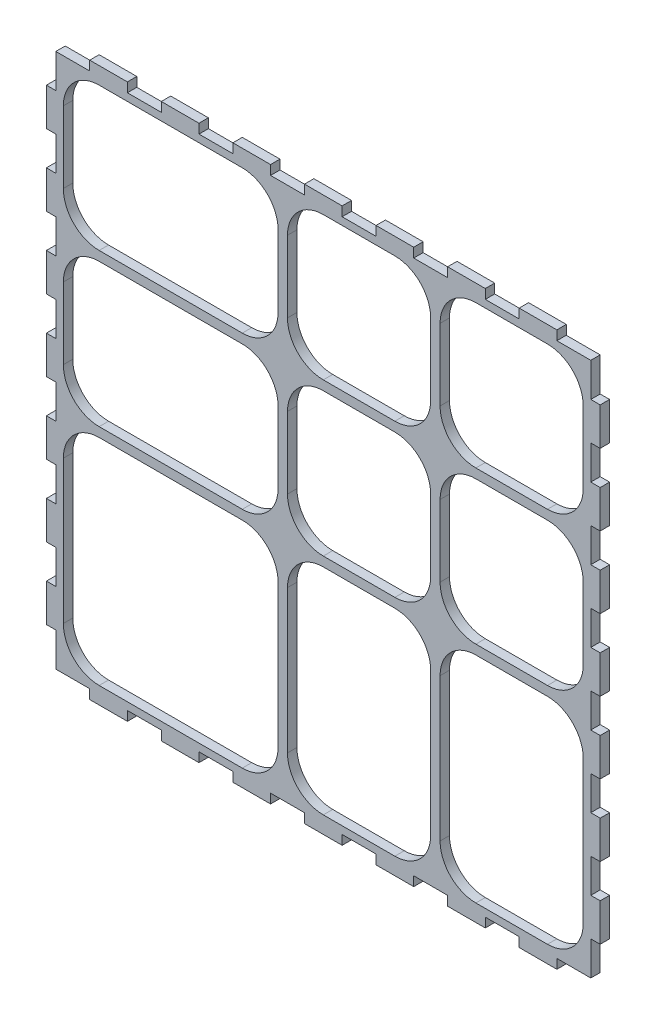
SolidWorks part; units mm, degrees
material "Beech"
ref_plane "Front" through (0, 0, 0) normal (0, 0, 1) x (1, 0, 0)
ref_plane "Top" through (0, 0, 0) normal (0, 1, 0) x (1, 0, 0)
ref_plane "Right" through (0, 0, 0) normal (1, 0, 0) x (0, 0, -1)
sketch "Sketch1" plane through (0, 0, 0) normal (0, 0, 1) x (1, 0, 0)
  line L0 (-71, 71) -> (71, 71) construction
  line L1 (-73.5, -73.5) -> (73.5, -73.5) construction
  line L2 (-73.5, -73.5) -> (-73.5, 73.5) construction
  line L3 (-73.5, 73.5) -> (73.5, 73.5) construction
  line L4 (73.5, -73.5) -> (73.5, 73.5) construction
  line L5 (-73.5, -73.5) -> (73.5, 73.5) construction
  line L6 (-73.5, 73.5) -> (73.5, -73.5) construction
  line L7 (71, -71) -> (71, 71) construction
  line L8 (-71, -71) -> (71, -71) construction
  line L9 (-71, -71) -> (-71, 71) construction
  line L10 (-73.5, 0) -> (-73.5, 5)
  line L11 (-73.5, 5) -> (-71, 5)
  line L12 (-71, 5) -> (-71, 14)
  line L13 (-71, 14) -> (-73.5, 14)
  line L14 (-73.5, 14) -> (-73.5, 24)
  line L15 (-73.5, 24) -> (-71, 24)
  line L16 (-71, 24) -> (-71, 33)
  line L17 (-71, 33) -> (-73.5, 33)
  line L18 (-73.5, 33) -> (-73.5, 43)
  line L19 (-73.5, 43) -> (-71, 43)
  line L20 (-71, 43) -> (-71, 52)
  line L21 (-71, 52) -> (-73.5, 52)
  line L22 (-73.5, 52) -> (-73.5, 62)
  line L23 (-73.5, 62) -> (-71, 62)
  line L24 (-71, 62) -> (-71, 71)
  line L25 (5, 73.5) -> (5, 71)
  line L26 (5, 71) -> (14, 71)
  line L27 (62, 71) -> (71, 71)
  line L28 (24, 71) -> (33, 71)
  line L29 (14, 73.5) -> (24, 73.5)
  line L30 (33, 73.5) -> (43, 73.5)
  line L31 (33, 71) -> (33, 73.5)
  line L32 (52, 71) -> (52, 73.5)
  line L33 (62, 73.5) -> (62, 71)
  line L34 (43, 73.5) -> (43, 71)
  line L35 (-5, 73.5) -> (5, 73.5)
  line L36 (24, 73.5) -> (24, 71)
  line L37 (14, 71) -> (14, 73.5)
  line L38 (43, 71) -> (52, 71)
  line L39 (52, 73.5) -> (62, 73.5)
  line L40 (0, 16.6882) -> (0, -16.401) construction
  line L41 (-21.4019, 0) -> (21.4019, 0) construction
  line L42 (71, 62) -> (71, 71)
  line L43 (73.5, 62) -> (71, 62)
  line L44 (73.5, 52) -> (73.5, 62)
  line L45 (71, 52) -> (73.5, 52)
  line L46 (71, 43) -> (71, 52)
  line L47 (73.5, 43) -> (71, 43)
  line L48 (73.5, 33) -> (73.5, 43)
  line L49 (71, 33) -> (73.5, 33)
  line L50 (71, 24) -> (71, 33)
  line L51 (73.5, 24) -> (71, 24)
  line L52 (73.5, 14) -> (73.5, 24)
  line L53 (71, 14) -> (73.5, 14)
  line L54 (71, 5) -> (71, 14)
  line L55 (73.5, 5) -> (71, 5)
  line L56 (73.5, 0) -> (73.5, 5)
  line L57 (-62, 71) -> (-71, 71)
  line L58 (-62, 73.5) -> (-62, 71)
  line L59 (-52, 73.5) -> (-62, 73.5)
  line L60 (-52, 71) -> (-52, 73.5)
  line L61 (-43, 71) -> (-52, 71)
  line L62 (-43, 73.5) -> (-43, 71)
  line L63 (-33, 73.5) -> (-43, 73.5)
  line L64 (-33, 71) -> (-33, 73.5)
  line L65 (-24, 71) -> (-33, 71)
  line L66 (-24, 73.5) -> (-24, 71)
  line L67 (-14, 73.5) -> (-24, 73.5)
  line L68 (-14, 71) -> (-14, 73.5)
  line L69 (-5, 71) -> (-14, 71)
  line L70 (-5, 73.5) -> (-5, 71)
  line L71 (73.5, 0) -> (73.5, -5)
  line L72 (73.5, -5) -> (71, -5)
  line L73 (71, -5) -> (71, -14)
  line L74 (71, -14) -> (73.5, -14)
  line L75 (73.5, -14) -> (73.5, -24)
  line L76 (73.5, -24) -> (71, -24)
  line L77 (71, -24) -> (71, -33)
  line L78 (71, -33) -> (73.5, -33)
  line L79 (73.5, -33) -> (73.5, -43)
  line L80 (73.5, -43) -> (71, -43)
  line L81 (71, -43) -> (71, -52)
  line L82 (71, -52) -> (73.5, -52)
  line L83 (73.5, -52) -> (73.5, -62)
  line L84 (73.5, -62) -> (71, -62)
  line L85 (71, -62) -> (71, -71)
  line L86 (62, -71) -> (71, -71)
  line L87 (62, -73.5) -> (62, -71)
  line L88 (52, -73.5) -> (62, -73.5)
  line L89 (52, -71) -> (52, -73.5)
  line L90 (43, -71) -> (52, -71)
  line L91 (43, -73.5) -> (43, -71)
  line L92 (33, -73.5) -> (43, -73.5)
  line L93 (33, -71) -> (33, -73.5)
  line L94 (24, -71) -> (33, -71)
  line L95 (24, -73.5) -> (24, -71)
  line L96 (14, -73.5) -> (24, -73.5)
  line L97 (14, -71) -> (14, -73.5)
  line L98 (5, -71) -> (14, -71)
  line L99 (5, -73.5) -> (5, -71)
  line L100 (-5, -73.5) -> (5, -73.5)
  line L101 (-5, -73.5) -> (-5, -71)
  line L102 (-5, -71) -> (-14, -71)
  line L103 (-14, -71) -> (-14, -73.5)
  line L104 (-14, -73.5) -> (-24, -73.5)
  line L105 (-24, -73.5) -> (-24, -71)
  line L106 (-24, -71) -> (-33, -71)
  line L107 (-33, -71) -> (-33, -73.5)
  line L108 (-33, -73.5) -> (-43, -73.5)
  line L109 (-43, -73.5) -> (-43, -71)
  line L110 (-43, -71) -> (-52, -71)
  line L111 (-52, -71) -> (-52, -73.5)
  line L112 (-52, -73.5) -> (-62, -73.5)
  line L113 (-62, -73.5) -> (-62, -71)
  line L114 (-62, -71) -> (-71, -71)
  line L115 (-71, -62) -> (-71, -71)
  line L116 (-73.5, -62) -> (-71, -62)
  line L117 (-73.5, -52) -> (-73.5, -62)
  line L118 (-71, -52) -> (-73.5, -52)
  line L119 (-71, -43) -> (-71, -52)
  line L120 (-73.5, -43) -> (-71, -43)
  line L121 (-73.5, -33) -> (-73.5, -43)
  line L122 (-71, -33) -> (-73.5, -33)
  line L123 (-71, -24) -> (-71, -33)
  line L124 (-73.5, -24) -> (-71, -24)
  line L125 (-73.5, -14) -> (-73.5, -24)
  line L126 (-71, -14) -> (-73.5, -14)
  line L127 (-71, -5) -> (-71, -14)
  line L128 (-73.5, -5) -> (-71, -5)
  line L129 (-73.5, 0) -> (-73.5, -5)
  line L130 (-9.5, 59.5) -> (-9.5, 40.5)
  line L131 (69, 69) -> (31, 69) construction
  line L132 (69, 69) -> (69, 31) construction
  line L133 (69, 31) -> (31, 31) construction
  line L134 (31, 69) -> (31, 31) construction
  line L135 (69, 69) -> (31, 31) construction
  line L136 (69, 31) -> (31, 69) construction
  line L137 (40.5, 69) -> (59.5, 69)
  line L138 (31, 59.5) -> (31, 40.5)
  line L139 (40.5, 31) -> (59.5, 31)
  line L140 (69, 59.5) -> (69, 40.5)
  line L141 (31, 69) -> (69, 31) construction
  line L142 (31, 31) -> (69, 69) construction
  line L143 (0, 69) -> (19, 69)
  line L144 (28.5, 59.5) -> (28.5, 40.5)
  line L145 (0, 31) -> (19, 31)
  line L146 (-9.5, 19) -> (-9.5, 0)
  line L147 (0, 28.5) -> (19, 28.5)
  line L148 (28.5, 19) -> (28.5, 0)
  line L149 (0, -9.5) -> (19, -9.5)
  line L150 (31, 19) -> (31, 0)
  line L151 (40.5, 28.5) -> (59.5, 28.5)
  line L152 (69, 19) -> (69, 0)
  line L153 (40.5, -9.5) -> (59.5, -9.5)
  line L154 (-69, 19) -> (-69, 0)
  line L155 (-69, 69) -> (-12, 69) construction
  line L156 (-69, 69) -> (-69, 31) construction
  line L157 (-69, 31) -> (-12, 31) construction
  line L158 (-12, 69) -> (-12, 31) construction
  line L159 (-69, 69) -> (-12, 31) construction
  line L160 (-69, 31) -> (-12, 69) construction
  line L161 (-59.5, 69) -> (-21.5, 69)
  line L162 (-69, 59.5) -> (-69, 40.5)
  line L163 (-59.5, 31) -> (-21.5, 31)
  line L164 (-12, 59.5) -> (-12, 40.5)
  line L165 (-69, 69) -> (-12, 31) construction
  line L166 (-69, 31) -> (-12, 69) construction
  line L167 (-59.5, 28.5) -> (-21.5, 28.5)
  line L168 (-12, 19) -> (-12, 0)
  line L169 (-59.5, -9.5) -> (-21.5, -9.5)
  line L170 (-9.5, -21.5) -> (-9.5, -59.5)
  line L171 (69, -69) -> (31, -69) construction
  line L172 (69, -69) -> (69, -12) construction
  line L173 (69, -12) -> (31, -12) construction
  line L174 (31, -69) -> (31, -12) construction
  line L175 (69, -69) -> (31, -12) construction
  line L176 (69, -12) -> (31, -69) construction
  line L177 (40.5, -12) -> (59.5, -12)
  line L178 (31, -21.5) -> (31, -59.5)
  line L179 (40.5, -69) -> (59.5, -69)
  line L180 (69, -21.5) -> (69, -59.5)
  line L181 (31, -12) -> (69, -69) construction
  line L182 (31, -69) -> (69, -12) construction
  line L183 (0, -12) -> (19, -12)
  line L184 (28.5, -21.5) -> (28.5, -59.5)
  line L185 (0, -69) -> (19, -69)
  line L187 (-69, -12) -> (-12, -12) construction
  line L188 (-69, -12) -> (-69, -69) construction
  line L189 (-69, -69) -> (-12, -69) construction
  line L190 (-12, -12) -> (-12, -69) construction
  line L191 (-69, -12) -> (-12, -69) construction
  line L192 (-69, -69) -> (-12, -12) construction
  line L193 (-59.5, -12) -> (-21.5, -12)
  line L194 (-69, -21.5) -> (-69, -59.5)
  line L195 (-59.5, -69) -> (-21.5, -69)
  line L196 (-12, -21.5) -> (-12, -59.5)
  line L197 (-69, -12) -> (-12, -69) construction
  line L198 (-69, -69) -> (-12, -12) construction
  arc A49 (59.5, 69) -> (69, 59.5) centre (59.5, 59.5) cw
  arc A50 (59.5, 31) -> (69, 40.5) centre (59.5, 40.5) ccw
  arc A51 (31, 40.5) -> (40.5, 31) centre (40.5, 40.5) ccw
  arc A52 (40.5, 69) -> (31, 59.5) centre (40.5, 59.5) ccw
  arc A53 (0, 69) -> (-9.5, 59.5) centre (0, 59.5) ccw
  arc A54 (-9.5, 40.5) -> (0, 31) centre (0, 40.5) ccw
  arc A55 (19, 69) -> (28.5, 59.5) centre (19, 59.5) cw
  arc A56 (19, 31) -> (28.5, 40.5) centre (19, 40.5) ccw
  arc A57 (0, 28.5) -> (-9.5, 19) centre (0, 19) ccw
  arc A58 (-9.5, 0) -> (0, -9.5) centre (0, 0) ccw
  arc A59 (19, 28.5) -> (28.5, 19) centre (19, 19) cw
  arc A60 (19, -9.5) -> (28.5, 0) centre (19, 0) ccw
  arc A61 (40.5, 28.5) -> (31, 19) centre (40.5, 19) ccw
  arc A62 (31, 0) -> (40.5, -9.5) centre (40.5, 0) ccw
  arc A63 (59.5, 28.5) -> (69, 19) centre (59.5, 19) cw
  arc A64 (59.5, -9.5) -> (69, 0) centre (59.5, 0) ccw
  arc A65 (-21.5, 31) -> (-12, 40.5) centre (-21.5, 40.5) ccw
  arc A66 (-21.5, 69) -> (-12, 59.5) centre (-21.5, 59.5) cw
  arc A67 (-59.5, 69) -> (-69, 59.5) centre (-59.5, 59.5) ccw
  arc A68 (-69, 40.5) -> (-59.5, 31) centre (-59.5, 40.5) ccw
  arc A69 (-69, 0) -> (-59.5, -9.5) centre (-59.5, 0) ccw
  arc A70 (-59.5, 28.5) -> (-69, 19) centre (-59.5, 19) ccw
  arc A71 (-21.5, 28.5) -> (-12, 19) centre (-21.5, 19) cw
  arc A72 (-21.5, -9.5) -> (-12, 0) centre (-21.5, 0) ccw
  arc A73 (59.5, -12) -> (69, -21.5) centre (59.5, -21.5) cw
  arc A74 (59.5, -69) -> (69, -59.5) centre (59.5, -59.5) ccw
  arc A75 (31, -59.5) -> (40.5, -69) centre (40.5, -59.5) ccw
  arc A76 (40.5, -12) -> (31, -21.5) centre (40.5, -21.5) ccw
  arc A77 (0, -12) -> (-9.5, -21.5) centre (0, -21.5) ccw
  arc A78 (-9.5, -59.5) -> (0, -69) centre (0, -59.5) ccw
  arc A79 (19, -12) -> (28.5, -21.5) centre (19, -21.5) cw
  arc A80 (19, -69) -> (28.5, -59.5) centre (19, -59.5) ccw
  arc A81 (-21.5, -69) -> (-12, -59.5) centre (-21.5, -59.5) ccw
  arc A82 (-69, -59.5) -> (-59.5, -69) centre (-59.5, -59.5) ccw
  arc A83 (-59.5, -12) -> (-69, -21.5) centre (-59.5, -21.5) ccw
  arc A84 (-21.5, -12) -> (-12, -21.5) centre (-21.5, -21.5) cw
  point P0 (0, 0)
  point P73 (0, 73.5)
  point P135 (50, 50)
  point P137 (50, 50)
  point P189 (-40.5, 50)
  point P191 (-40.5, 50)
  point P219 (50, -40.5)
  point P222 (50, -40.5)
  point P249 (-40.5, -40.5)
  point P251 (-40.5, -40.5)
  dimension "D7" = 2
  dimension "D10" = 9.5
  dimension "D17" = 9.5
  dimension "D21" = 9.5
  dimension "D23" = 9.5
  dimension "D24" = 9.5
  dimension "D1" = 147
  dimension "D3" = 10
  dimension "D4" = 9
  dimension "D5" = 9
  dimension "D6" = 10
  dimension "D8" = 2
  dimension "D9" = 38
  dimension "D12" = 38
  dimension "D13" = 57
  dimension "D15" = 2
  dimension "D16" = 2
  dimension "D19" = 2
  dimension "D20" = 57
  dimension "D25" = 2.5
  dimension "D26" = 2.5
  dimension "D2" = 2.5
  dimension "D14" = 2
  dimension "D11" = 2
  dimension "D18" = 2
  dimension "D22" = 2
extrude "Boss-Extrude1" add sketch "Sketch1" along normal blind 2.5
